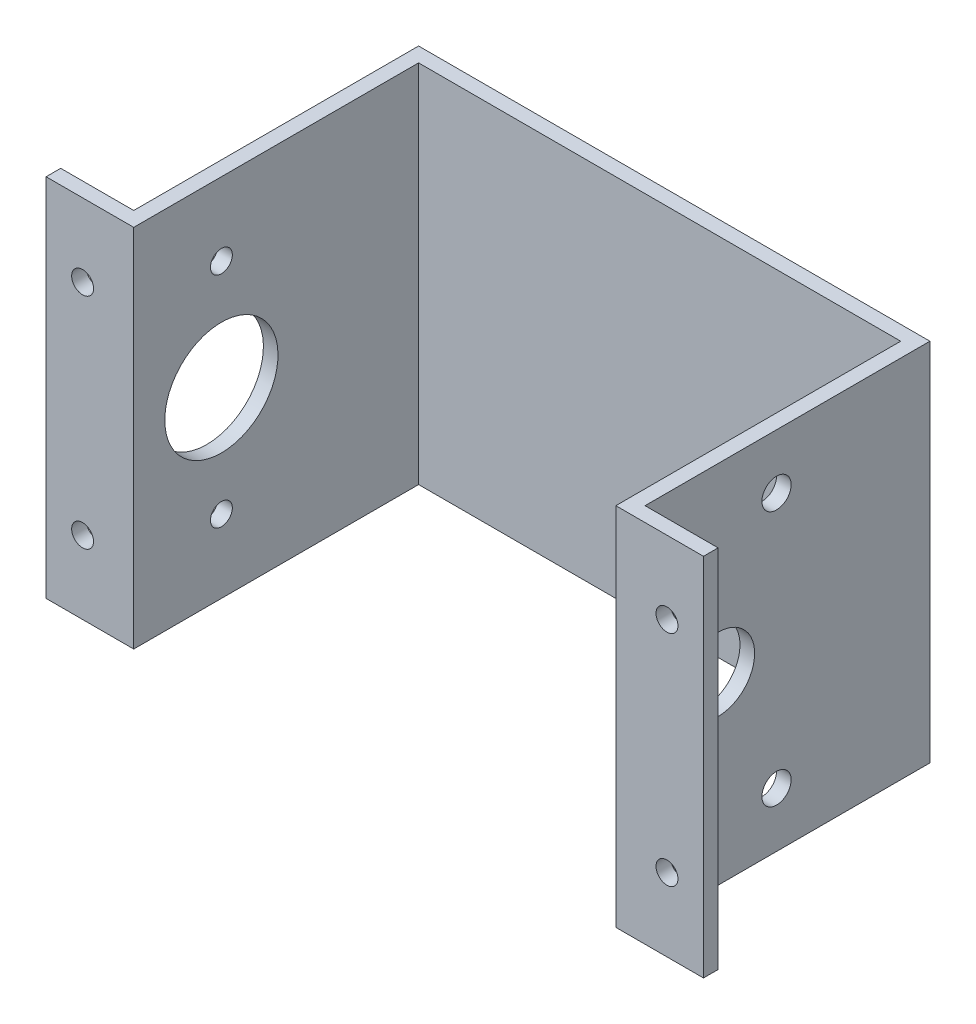
SolidWorks part; units mm, degrees
ref_plane "Front Plane" through (0, 0, 0) normal (0, 0, 1) x (1, 0, 0)
ref_plane "Top Plane" through (0, 0, 0) normal (0, 1, 0) x (1, 0, 0)
ref_plane "Right Plane" through (0, 0, 0) normal (1, 0, 0) x (0, 0, -1)
sketch "Sketch1" plane through (0, 0, 0) normal (0, 0, 1) x (1, 0, 0)
  line L1 (35, 25) -> (-35, 25)
  line L2 (35, 25) -> (35, -25)
  line L3 (35, -25) -> (-35, -25)
  line L4 (-35, 25) -> (-35, -25)
  line L5 (35, 25) -> (-35, -25) construction
  line L6 (35, -25) -> (-35, 25) construction
  point P0 (0, 0)
  dimension "D1" = 70
  dimension "D2" = 50
extrude "Boss-Extrude1" add sketch "Sketch1" along normal blind 2
sketch "Sketch2" plane through (0, 0, 2) normal (0, 0, 1) x (1, 0, 0)
  line L0 (-35, -25) -> (35, -25) construction
  line L1 (35, 25) -> (33, 25)
  line L2 (35, 25) -> (35, -25)
  line L3 (35, -25) -> (33, -25)
  line L4 (33, 25) -> (33, -25)
  line L6 (-35, 25) -> (-33, 25)
  line L7 (-35, 25) -> (-35, -25)
  line L8 (-35, -25) -> (-33, -25)
  line L9 (-33, 25) -> (-33, -25)
  dimension "D1" = 2
  dimension "D2" = 2
extrude "Boss-Extrude2" add sketch "Sketch2" along normal blind 37
sketch "Sketch3" plane through (0, 0, 39) normal (0, 0, 1) x (1, 0, 0)
  line L0 (33, -25) -> (35, -25) construction
  line L1 (33, 25) -> (45, 25)
  line L2 (33, 25) -> (33, -25)
  line L3 (33, -25) -> (45, -25)
  line L4 (45, 25) -> (45, -25)
  line L5 (-35, -25) -> (-33, -25) construction
  line L6 (-33, 25) -> (-45, 25)
  line L7 (-33, 25) -> (-33, -25)
  line L8 (-33, -25) -> (-45, -25)
  line L9 (-45, 25) -> (-45, -25)
  dimension "D1" = 12
  dimension "D2" = 12
extrude "Boss-Extrude3" add sketch "Sketch3" along normal blind 2
sketch "Sketch4" plane through (35, 0, 0) normal (1, 0, 0) x (0, 0, -1)
  line L1 (-39, -25) -> (-39, 25) construction
  line L2 (0, 0) -> (-39, 0) construction
  line L3 (0, -25) -> (0, 25) construction
  circle A0 centre (-29, 0) radius 5
  circle A1 centre (-21, 17.5) radius 2
  circle A2 centre (-21, -17.5) radius 2
  dimension "D1" = 10
  dimension "D2" = 0
  dimension "D3" = 10
  dimension "D4" = 8
  dimension "D5" = 8
  dimension "D6" = 4
  dimension "D7" = 4
  dimension "D8" = 35
  dimension "D9" = 17.5
extrude "Cut-Extrude1" cut sketch "Sketch4" against normal blind 2
sketch "Sketch5" plane through (-35, 0, 0) normal (-1, 0, 0) x (0, 0, 1)
  line L0 (39, 25) -> (39, -25) construction
  line L2 (0, 0) -> (16.8475, 0) construction
  line L3 (0, 25) -> (0, -25) construction
  circle A0 centre (29, 0) radius 7.75
  circle A1 centre (29, 15) radius 1.5
  circle A2 centre (29, -15) radius 1.5
  dimension "D1" = 10
  dimension "D2" = 15.5
  dimension "D4" = 30
  dimension "D5" = 15
  dimension "D6" = 10
  dimension "D7" = 10
  dimension "D8" = 3
  dimension "D9" = 3
  dimension "D3" = 0
extrude "Cut-Extrude2" cut sketch "Sketch5" against normal blind 2
sketch "Sketch6" plane through (0, 0, 39) normal (0, 0, -1) x (-1, 0, 0)
  line L0 (-45, 25) -> (-35, 25) construction
  line L1 (-45, -25) -> (-45, 25) construction
  line L2 (0, 0) -> (-45, 0) construction
  line L3 (0, 25) -> (0, 0) construction
  line L4 (-35, 25) -> (35, 25) construction
  circle A0 centre (-40, 15) radius 1.5
  circle A1 centre (-40, -15) radius 1.5
  circle A2 centre (40, -15) radius 1.5
  circle A3 centre (40, 15) radius 1.5
  dimension "D1" = 3
  dimension "D2" = 10
  dimension "D3" = 5
extrude "Cut-Extrude3" cut sketch "Sketch6" against normal blind 2
